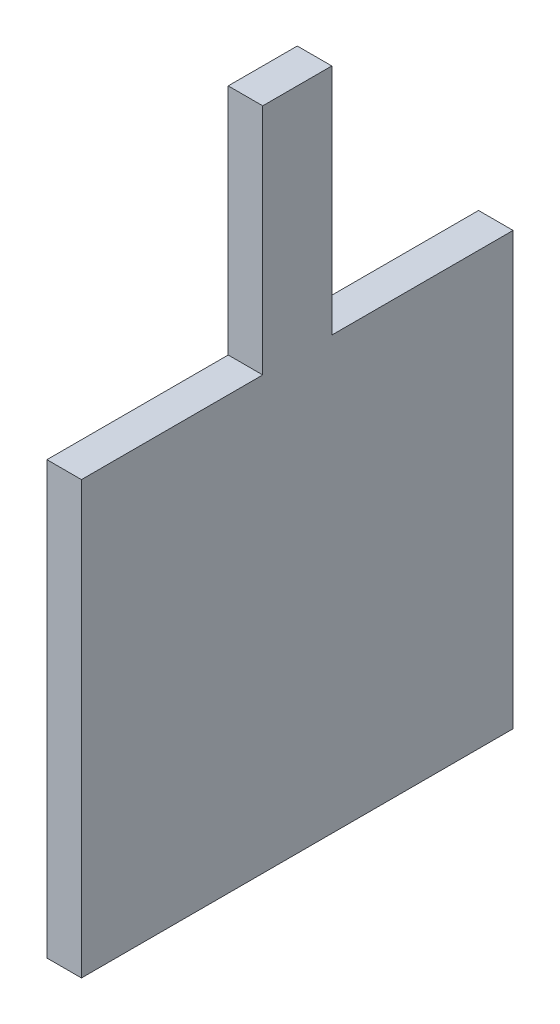
SolidWorks part; units mm, degrees
ref_plane "Front Plane" through (0, 0, 0) normal (0, 0, 1) x (1, 0, 0)
ref_plane "Top Plane" through (0, 0, 0) normal (0, 1, 0) x (1, 0, 0)
ref_plane "Right Plane" through (0, 0, 0) normal (1, 0, 0) x (0, 0, -1)
sketch "Sketch1" plane through (0, 0, 0) normal (1, 0, 0) x (0, 0, -1)
  line L0 (0, 0) -> (0, 27)
  line L1 (0, 27) -> (8, 27)
  line L2 (8, 27) -> (8, 0)
  line L3 (8, 0) -> (29, 0)
  line L4 (29, 0) -> (29, -50)
  line L5 (29, -50) -> (-21, -50)
  line L6 (-21, -50) -> (-21, 0)
  line L7 (-21, 0) -> (0, 0)
  dimension "D1" = 21
  dimension "D2" = 27
  dimension "D3" = 8
  dimension "D4" = 50
extrude "Boss-Extrude1" add sketch "Sketch1" along normal blind 4
